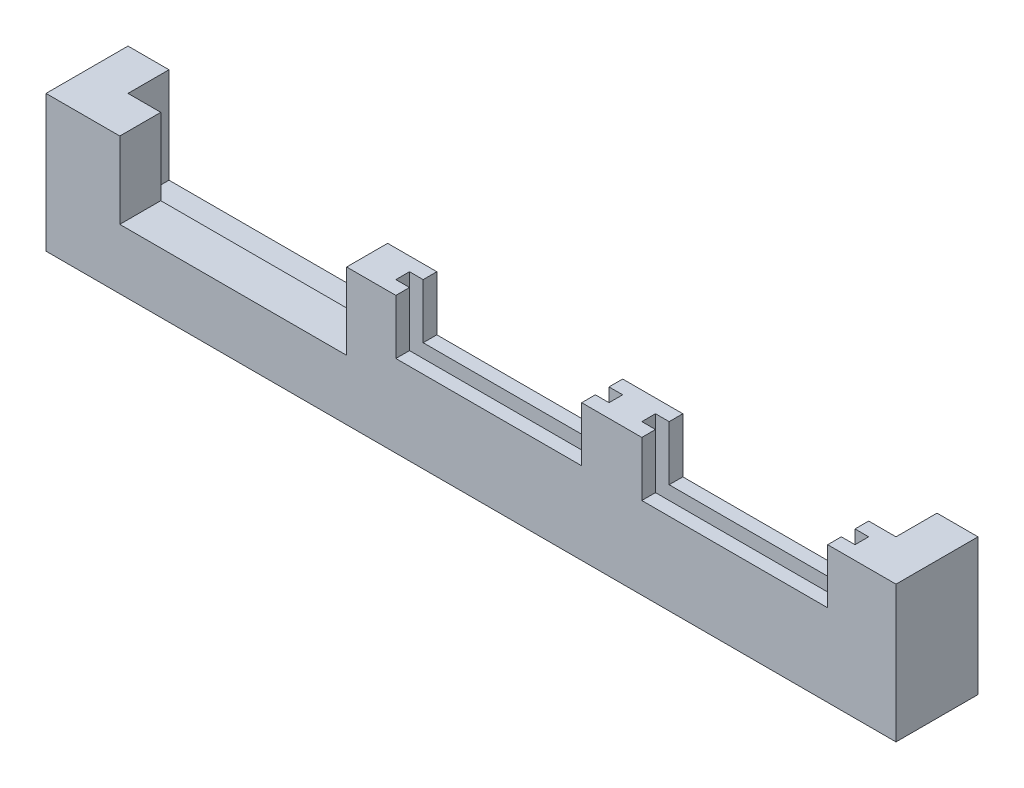
SolidWorks part; units mm, degrees
ref_plane "Front" through (0, 0, 0) normal (0, 0, 1) x (1, 0, 0)
ref_plane "Top" through (0, 0, 0) normal (0, 1, 0) x (1, 0, 0)
ref_plane "Right" through (0, 0, 0) normal (1, 0, 0) x (0, 0, -1)
sketch "Sketch1" plane through (0, 0, 0) normal (0, 0, 1) x (1, 0, 0)
  line L0 (-26.3783, -16.4423) -> (29.8217, -16.4423) construction
  line L2 (29.8217, -20.8423) -> (-26.3783, -20.8423)
  line L3 (29.8217, -20.8423) -> (29.8217, -10.8423) construction
  line L4 (29.8217, -10.8423) -> (27.8217, -10.8423)
  line L5 (-26.3783, -20.8423) -> (-26.3783, -10.8423) construction
  line L6 (-23.9783, -10.8423) -> (-23.9783, -16.4423)
  line L7 (-23.9783, -16.4423) -> (-7.3783, -16.4423)
  line L8 (-7.3783, -10.8423) -> (-7.3783, -16.4423)
  line L9 (-26.3783, -17.8423) -> (29.8217, -17.8423) construction
  line L10 (-26.3783, -20.8423) -> (-29.3783, -20.8423)
  line L11 (-3.7783, -10.8423) -> (-7.3783, -10.8423)
  line L13 (-3.7783, -10.8423) -> (-3.7783, -14.8423)
  line L14 (-3.7783, -14.8423) -> (9.8217, -14.8423)
  line L15 (9.8217, -10.8423) -> (9.8217, -14.8423)
  line L17 (14.2217, -10.8423) -> (14.2217, -14.8423)
  line L18 (14.2217, -14.8423) -> (27.8217, -14.8423)
  line L19 (27.8217, -10.8423) -> (27.8217, -14.8423)
  line L20 (14.2217, -10.8423) -> (9.8217, -10.8423)
  line L21 (-23.9783, -10.8423) -> (-26.3783, -10.8423)
  line L22 (-29.3783, -20.8423) -> (-29.3783, -10.8423)
  line L23 (-29.3783, -10.8423) -> (-26.3783, -10.8423)
  line L24 (29.8217, -10.8423) -> (32.8217, -10.8423)
  line L25 (32.8217, -10.8423) -> (32.8217, -20.8423)
  line L26 (32.8217, -20.8423) -> (29.8217, -20.8423)
  dimension "D1" = 2.4
  dimension "D2" = 10
  dimension "D3" = 1.4
  dimension "D4" = 62.2
  dimension "D5" = 3.6
  dimension "D6" = 16.6
  dimension "D7" = 13.6
  dimension "D8" = 4.4
  dimension "D9" = 3
  dimension "D10" = 3
  dimension "D11" = 3
  dimension "D12" = 3
extrude "Boss-Extrude1" add sketch "Sketch1" along normal blind 3 contours L4 L19 L18 L17 L20 L15 L14 L13 L11 L8 L7 L6 L21 L23 L22 L10 L2 L26 L25 L24
sketch "Sketch4" plane through (0, -10.8423, 0) normal (0, 1, 0) x (1, 0, 0)
  line L0 (-4.7783, -1.5) -> (10.8217, -1.5) construction
  line L1 (-4.7783, -1) -> (10.8217, -1)
  line L2 (-4.7783, -1) -> (-4.7783, -2)
  line L3 (-4.7783, -2) -> (10.8217, -2)
  line L4 (28.8217, -1) -> (28.8217, -2)
  line L7 (-3.7783, -3) -> (-3.7783, 0) construction
  line L8 (27.8217, -3) -> (27.8217, 0) construction
  line L9 (10.8217, -1) -> (10.8217, -2)
  line L10 (13.2217, -1) -> (13.2217, -2)
  line L11 (9.8217, -3) -> (9.8217, 0) construction
  line L12 (14.2217, -3) -> (14.2217, 0) construction
  line L13 (13.2217, -1.5) -> (28.8217, -1.5) construction
  line L14 (13.2217, -1) -> (28.8217, -1)
  line L15 (13.2217, -2) -> (28.8217, -2)
  line L16 (12.0217, 0) -> (12.0217, -3) construction
  line L17 (14.2217, 0) -> (9.8217, 0) construction
  line L18 (14.2217, -3) -> (9.8217, -3) construction
  line L19 (12.0217, -1.5) -> (13.2217, -1.5) construction
  point P10 (-4.7783, -1.5)
  dimension "D1" = 1
  dimension "D2" = 1
  dimension "D3" = 1
  dimension "D4" = 1
  dimension "D5" = 1
extrude "Cut-Extrude1" cut sketch "Sketch4" against normal offset from surface (5 mm away) 1 up to face at (3.0217, -14.8423, 1.5) offset beyond the face yes
sketch "Sketch5" plane through (0, 0, 0) normal (0, 0, -1) x (-1, 0, 0)
  line L0 (-32.8217, -10.8423) -> (-32.8217, -20.8423)
  line L1 (-32.8217, -20.8423) -> (29.3783, -20.8423)
  line L2 (29.3783, -20.8423) -> (29.3783, -10.8423)
  line L3 (29.3783, -10.8423) -> (26.3783, -10.8423)
  line L4 (23.9783, -10.8423) -> (29.3783, -10.8423) construction
  line L5 (26.3783, -10.8423) -> (26.3783, -17.8423)
  line L6 (26.3783, -17.8423) -> (-29.8217, -17.8423)
  line L7 (-29.8217, -17.8423) -> (-29.8217, -10.8423)
  line L8 (-32.8217, -10.8423) -> (-27.8217, -10.8423) construction
  line L9 (-29.8217, -10.8423) -> (-32.8217, -10.8423)
  point P16 (0, 0)
  dimension "D1" = 3
  dimension "D2" = 3
  dimension "D3" = 3
extrude "Boss-Extrude3" add sketch "Sketch5" along normal blind 3
